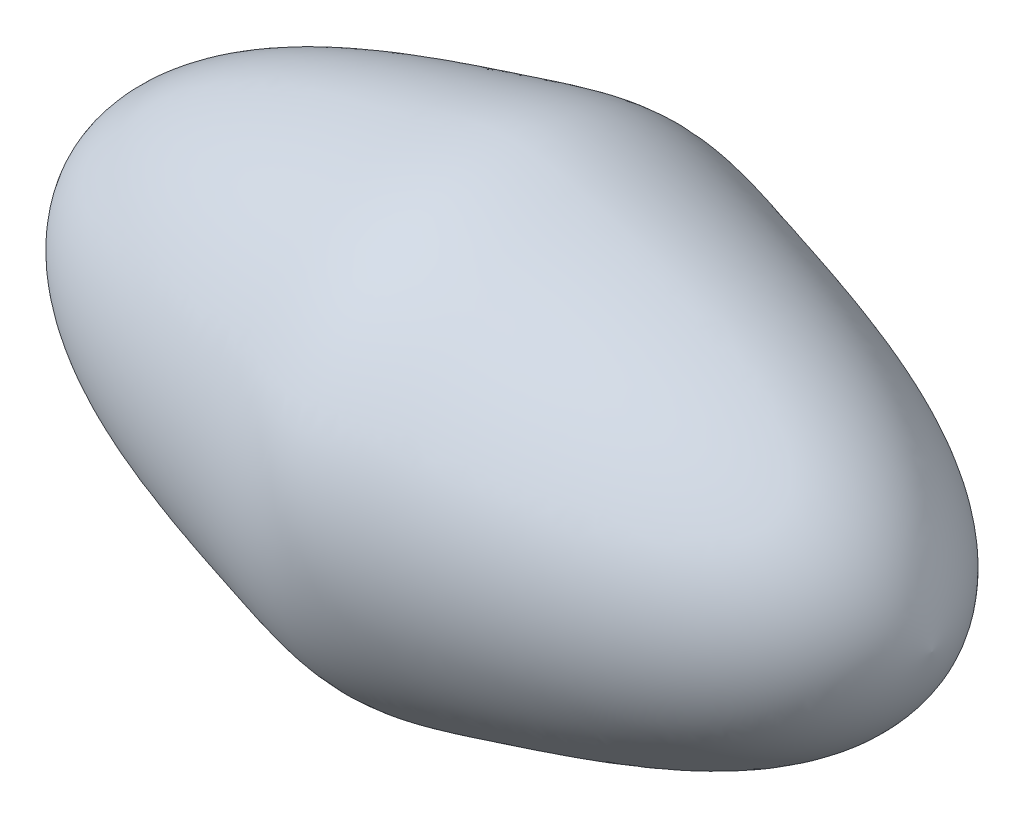
SolidWorks part; units mm, degrees
ref_plane "前视基准面" through (0, 0, 0) normal (0, 0, 1) x (1, 0, 0)
ref_plane "上视基准面" through (0, 0, 0) normal (0, 1, 0) x (1, 0, 0)
ref_plane "右视基准面" through (0, 0, 0) normal (1, 0, 0) x (0, 0, -1)
sketch "草图2" plane through (0, 0, 0) normal (0, 0, 1) x (1, 0, 0)
  line L0 (0, 0) -> (9, 0)
  line L1 (4.5, 0) -> (4.5, 2.5) construction
  spline S0 degree 3 poles (0, 0) (0.2247, 1.4625) (2.4725, 2.0352) (4.5, 2.5881) (6.5275, 2.0352) (8.7753, 1.4625) (9, 0) knots 0 0 0 0 0.405211 0.5 0.594789 1 1 1 1
  point P8 (0, 0)
  point P10 (0, 0)
  point P12 (2.8342, 2.2101)
  point P13 (0.9314, 0.9111)
  point P14 (3.072, 2.1003)
  point P15 (3.5111, 2.3199)
  point P16 (0.4923, 0.6)
  point P17 (0.0726, 0.3005)
  dimension "D1" = 9
  dimension "D2" = 2.5
revolve "旋转1" add sketch "草图2" angle 360 about L0
